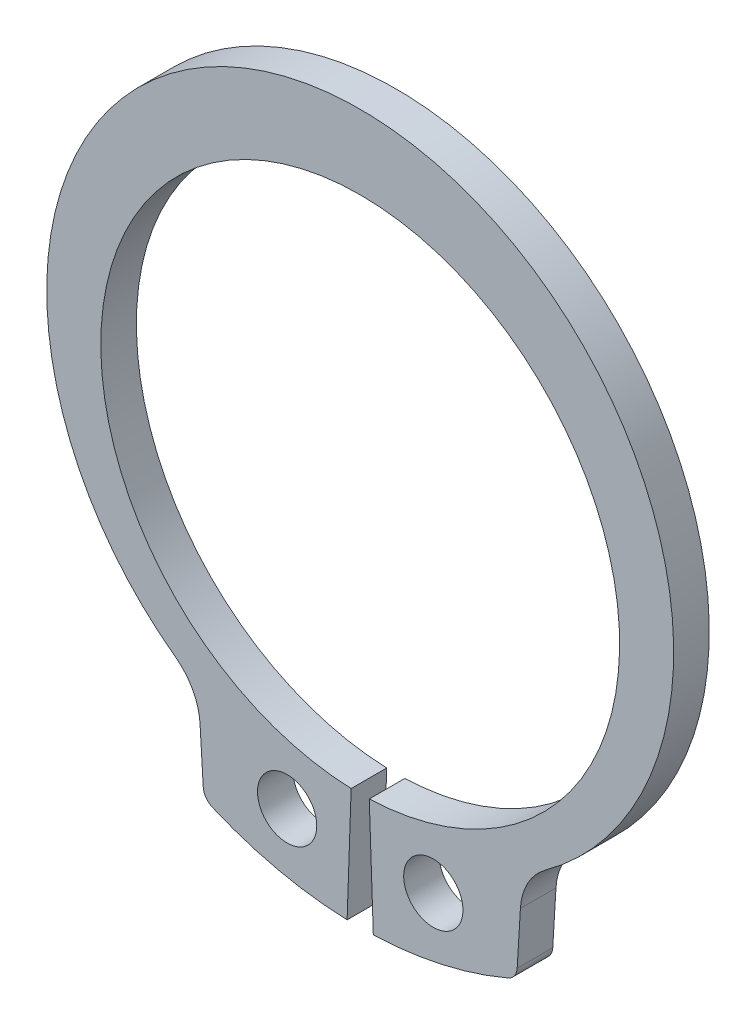
SolidWorks part; units mm, degrees
material "Plain Carbon Steel"
ref_plane "Front" through (0, 0, 0) normal (0, 0, 1) x (1, 0, 0)
ref_plane "Top" through (0, 0, 0) normal (0, 1, 0) x (1, 0, 0)
ref_plane "Right" through (0, 0, 0) normal (1, 0, 0) x (0, 0, -1)
sketch "Sketch1" plane through (0, 0, 0) normal (0, 0, 1) x (1, 0, 0)
  line L0 (0, 0) -> (-7.5777, -4.375) construction
  line L1 (0, 12.65) -> (0, -12.65) construction
  line L2 (-5.2757, -11.5058) -> (-5.4641, -8.3752) construction
  line L4 (-5.4641, -8.3752) -> (-6.1471, -9.4221) construction
  line L5 (-5.4641, -8.3752) -> (0, 0) construction
  line L6 (0, 8.75) -> (0, 11.25) construction
  line L7 (0, 11.25) -> (0, 10) construction
  line L8 (0, -8.75) -> (0, -12.65) construction
  line L9 (-2.9154, -12.3174) -> (0, 0) construction
  line L10 (0, 0) -> (-0.4417, -12.65) construction
  line L11 (-5.2757, -11.5058) -> (0, 0) construction
  line L12 (-5.4082, -9.3043) -> (-6.239, -7.8595) construction
  line L13 (-5.8236, -8.5819) -> (-5.4641, -8.3752) construction
  line L14 (-2.0154, -8.5147) -> (-2.9154, -12.3174) construction
  line L15 (-2.4654, -10.4161) -> (-1.4923, -10.6464) construction
  arc A0 (0, 11.25) -> (-5.4641, -8.3752) centre (0, 0.6767) ccw construction
  circle A2 centre (0, 0) radius 11.25 construction
  arc A3 (-5.2757, -11.5058) -> (-0.4417, -12.65) centre (0, 0) ccw construction
  circle A4 centre (0, 0) radius 8.75 construction
  circle A6 centre (-2.4654, -10.4161) radius 1 construction
  arc A7 (-6.239, -7.8595) -> (-5.4082, -9.3043) centre (-7.4511, -9.5178) cw construction
  circle A9 centre (0, 0) radius 9.5 construction
  circle A10 centre (0, 0) radius 9 construction
  point P5 (-7.5777, -4.375)
  point P24 (-4.689, -10.2262)
  point P35 (0, 11.25)
  point P36 (0, 8.75)
  point P37 (0, -8.75)
  point P38 (0, -12.65)
  dimension "Hole Diameter" = 2
  dimension "D10" = 2.054
  dimension "For OD" = 19
  dimension "ID" = 17.5
  dimension "Max Sec." = 2.5
  dimension "Lug Height" = 3.9
  dimension "D6" = 2
  dimension "D5" = 3.1363
  dimension "D8" = 1.6667
  dimension "D3" = 120
  dimension "D2" = 5
  dimension "D4" = 1.6667
sketch "Sketch2" plane through (0, 0, 0) normal (-1, 0, 0) x (0, 1, 0)
  line L0 (-11.25, 0.6) -> (-11.25, -0.6) construction
  line L1 (11.25, -0.65) -> (11.25, 0.65) construction
  line L2 (0, 0.6) -> (0, -0.6) construction
  line L4 (-11.25, 0) -> (11.25, 0) construction
  point P3 (-11.25, 0)
  point P6 (0, 0)
  point P14 (11.25, 0)
  dimension "Thickness" = 1.2
  dimension "For Groove Width" = 1.3
sketch "Sketch4" plane through (0, 0, 0) normal (0, 0, 1) x (1, 0, 0)
  line L0 (-5.2757, -11.5058) -> (-5.4641, -8.3752) construction
  line L1 (-5.2757, -11.5058) -> (-5.4641, -8.3752)
  line L2 (0, 11.25) -> (0, 8.75)
  line L3 (-0.4417, -12.65) -> (-0.3054, -8.7447)
  line L4 (0, 0) -> (-0.4417, -12.65) construction
  arc A0 (0, 11.25) -> (-5.4641, -8.3752) centre (0, 0.6767) ccw construction
  arc A1 (-5.2757, -11.5058) -> (-0.4417, -12.65) centre (0, 0) ccw construction
  circle A2 centre (-2.4654, -10.4161) radius 1 construction
  arc A4 (0, 11.25) -> (-5.4641, -8.3752) centre (0, 0.6767) ccw
  arc A5 (-5.2757, -11.5058) -> (-0.4417, -12.65) centre (0, 0) ccw
  circle A6 centre (-2.4654, -10.4161) radius 1
  circle A7 centre (0, 0) radius 8.75 construction
  arc A8 (0, 8.75) -> (-0.3054, -8.7447) centre (0, 0) ccw
extrude "Boss-Extrude1" add sketch "Sketch4" along normal mid plane 1.2
fillet "Fillet1" radius 2.054 1 edges at (-5.4641, -8.3752, 0)
fillet "Fillet2" radius 0.5135 1 edges at (-5.2757, -11.5058, 0)
mirror "Mirror1" about plane through (0, 11.25, 0.6) normal (-1, 0, 0) of bodies 109
sketch "Sketch3" plane through (0, 0, 0.6) normal (0, 0, 1) x (1, 0, 0)
  line L0 (5.4817, -6.8201) -> (6.2408, -7.8583) construction
  line L1 (6.2408, -7.8583) -> (7.279, -7.0991) construction
  line L2 (0, 11.25) -> (0, 8.75) construction
  circle A0 centre (0, 0) radius 8.75 construction
  arc A1 (6.2408, -7.8583) -> (-6.2408, -7.8583) centre (0, 0.6767) ccw construction
equation "\"D1@Fillet1\" = \"D10@Sketch1\""
equation "\"D1@Fillet2\" = \"D10@Sketch1\" / 4"
equation "\"Thickness@Boss-Extrude1\"  = \"Ring Thickness@Sketch5\""
equation "\"D2@Sketch1\"=\"Hole Diameter@Sketch1\"*2.5"
equation "\"D4@Sketch1\"=\"D2@Sketch1\"/3"
equation "\"D8@Sketch1\"=\"D4@Sketch1\""
